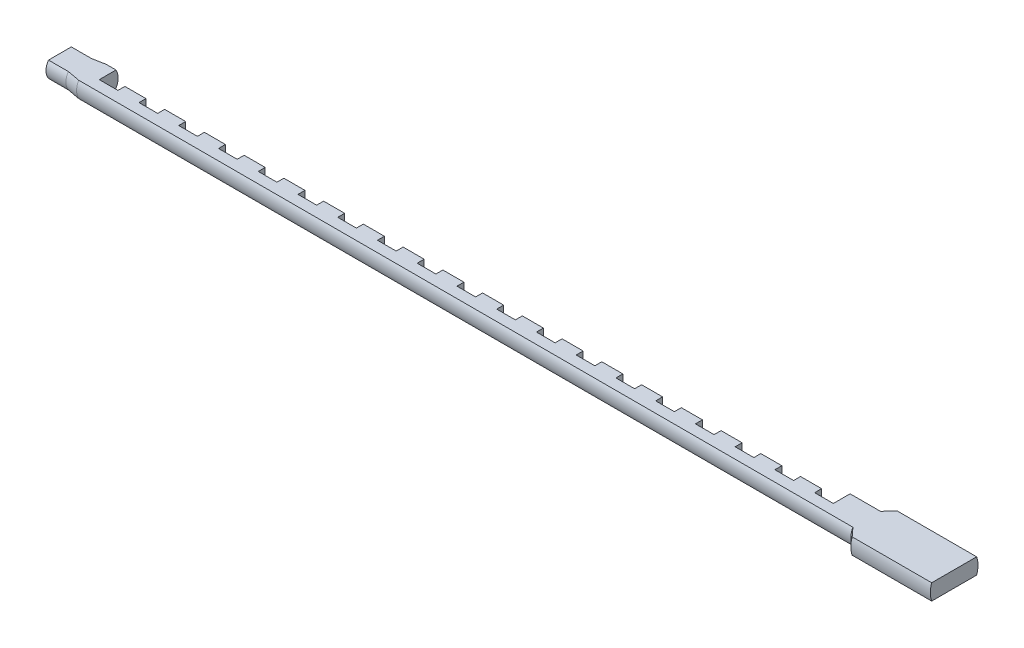
SolidWorks part; units mm, degrees
ref_plane "Front Plane" through (0, 0, 0) normal (0, 0, 1) x (1, 0, 0)
ref_plane "Top Plane" through (0, 0, 0) normal (0, 1, 0) x (1, 0, 0)
ref_plane "Right Plane" through (0, 0, 0) normal (1, 0, 0) x (0, 0, -1)
other "Configuration Table"
sketch "Sketch1" plane through (0, 0, 0) normal (0, 1, 0) x (1, 0, 0)
  line L0 (-125, 0) -> (100, 0) construction
  line L1 (-125, 0) -> (-125, 3.5)
  line L2 (-125, 3.5) -> (-120, 3.5)
  line L3 (-120, 3.5) -> (-116.8027, 4)
  line L4 (-116.8027, 4) -> (78, 4)
  line L6 (80, 6) -> (100, 6)
  line L7 (100, 6) -> (100, 0)
  line L8 (100, 0) -> (-125, 0)
  line L9 (78, 4) -> (80, 6)
  point P3 (90.4375, 2.5)
  point P10 (95.0649, 2.5)
  dimension "D1" = 125
  dimension "D2" = 100
  dimension "D3" = 3.5
  dimension "D4" = 5
  dimension "D5" = 4
  dimension "D6" = 20
  dimension "D7" = 6
  dimension "D8" = 45
revolve "Revolve1" add sketch "Sketch1" angle 360 about L0
sketch "Sketch3" plane through (0, 0, 0) normal (0, 1, 0) x (1, 0, 0)
  line L0 (-114.35, 4) -> (-114.35, -0.75)
  line L1 (78, 4) -> (-116.8027, 4) construction
  line L2 (-114.35, -0.75) -> (-109.65, -0.75)
  line L3 (-109.65, -0.75) -> (-109.65, 4)
  line L4 (-109.65, 4) -> (-114.35, 4)
  line L5 (-114.35, 4) -> (-109.65, -0.75) construction
  line L6 (-109.65, 4) -> (-114.35, -0.75) construction
  line L7 (-125, 3.5) -> (-125, -3.5) construction
  line L8 (-99.65, 4) -> (-104.35, 4)
  line L9 (-104.35, 4) -> (-104.35, -0.75)
  line L10 (-104.35, -0.75) -> (-99.65, -0.75)
  line L11 (-99.65, -0.75) -> (-99.65, 4)
  line L12 (-89.65, 4) -> (-94.35, 4)
  line L13 (-94.35, 4) -> (-94.35, -0.75)
  line L14 (-94.35, -0.75) -> (-89.65, -0.75)
  line L15 (-89.65, -0.75) -> (-89.65, 4)
  line L16 (-79.65, 4) -> (-84.35, 4)
  line L17 (-84.35, 4) -> (-84.35, -0.75)
  line L18 (-84.35, -0.75) -> (-79.65, -0.75)
  line L19 (-79.65, -0.75) -> (-79.65, 4)
  line L20 (-69.65, 4) -> (-74.35, 4)
  line L21 (-74.35, 4) -> (-74.35, -0.75)
  line L22 (-74.35, -0.75) -> (-69.65, -0.75)
  line L23 (-69.65, -0.75) -> (-69.65, 4)
  line L24 (-59.65, 4) -> (-64.35, 4)
  line L25 (-64.35, 4) -> (-64.35, -0.75)
  line L26 (-64.35, -0.75) -> (-59.65, -0.75)
  line L27 (-59.65, -0.75) -> (-59.65, 4)
  line L28 (-49.65, 4) -> (-54.35, 4)
  line L29 (-54.35, 4) -> (-54.35, -0.75)
  line L30 (-54.35, -0.75) -> (-49.65, -0.75)
  line L31 (-49.65, -0.75) -> (-49.65, 4)
  line L32 (-39.65, 4) -> (-44.35, 4)
  line L33 (-44.35, 4) -> (-44.35, -0.75)
  line L34 (-44.35, -0.75) -> (-39.65, -0.75)
  line L35 (-39.65, -0.75) -> (-39.65, 4)
  line L36 (-29.65, 4) -> (-34.35, 4)
  line L37 (-34.35, 4) -> (-34.35, -0.75)
  line L38 (-34.35, -0.75) -> (-29.65, -0.75)
  line L39 (-29.65, -0.75) -> (-29.65, 4)
  line L40 (-19.65, 4) -> (-24.35, 4)
  line L41 (-24.35, 4) -> (-24.35, -0.75)
  line L42 (-24.35, -0.75) -> (-19.65, -0.75)
  line L43 (-19.65, -0.75) -> (-19.65, 4)
  line L44 (-9.65, 4) -> (-14.35, 4)
  line L45 (-14.35, 4) -> (-14.35, -0.75)
  line L46 (-14.35, -0.75) -> (-9.65, -0.75)
  line L47 (-9.65, -0.75) -> (-9.65, 4)
  line L48 (0.35, 4) -> (-4.35, 4)
  line L49 (-4.35, 4) -> (-4.35, -0.75)
  line L50 (-4.35, -0.75) -> (0.35, -0.75)
  line L51 (0.35, -0.75) -> (0.35, 4)
  line L52 (10.35, 4) -> (5.65, 4)
  line L53 (5.65, 4) -> (5.65, -0.75)
  line L54 (5.65, -0.75) -> (10.35, -0.75)
  line L55 (10.35, -0.75) -> (10.35, 4)
  line L56 (20.35, 4) -> (15.65, 4)
  line L57 (15.65, 4) -> (15.65, -0.75)
  line L58 (15.65, -0.75) -> (20.35, -0.75)
  line L59 (20.35, -0.75) -> (20.35, 4)
  line L60 (30.35, 4) -> (25.65, 4)
  line L61 (25.65, 4) -> (25.65, -0.75)
  line L62 (25.65, -0.75) -> (30.35, -0.75)
  line L63 (30.35, -0.75) -> (30.35, 4)
  line L64 (40.35, 4) -> (35.65, 4)
  line L65 (35.65, 4) -> (35.65, -0.75)
  line L66 (35.65, -0.75) -> (40.35, -0.75)
  line L67 (40.35, -0.75) -> (40.35, 4)
  line L68 (50.35, 4) -> (45.65, 4)
  line L69 (45.65, 4) -> (45.65, -0.75)
  line L70 (45.65, -0.75) -> (50.35, -0.75)
  line L71 (50.35, -0.75) -> (50.35, 4)
  line L72 (60.35, 4) -> (55.65, 4)
  line L73 (55.65, 4) -> (55.65, -0.75)
  line L74 (55.65, -0.75) -> (60.35, -0.75)
  line L75 (60.35, -0.75) -> (60.35, 4)
  line L76 (70.35, 4) -> (65.65, 4)
  line L77 (65.65, 4) -> (65.65, -0.75)
  line L78 (65.65, -0.75) -> (70.35, -0.75)
  line L79 (70.35, -0.75) -> (70.35, 4)
  point P4 (-112, 1.625)
  dimension "D1" = 0.75
  dimension "D2" = 4.7
  dimension "D3" = 13
  dimension "D4" = 19
extrude "Cut-Extrude1" cut sketch "Sketch3" against normal through all both and the other way through all
sketch "Sketch4" plane through (0, 0, 0) normal (0, 1, 0) x (1, 0, 0)
  line L0 (70.35, 4) -> (70.35, -0.75) construction
  line L1 (-114.35, 4) -> (70.35, 4)
  line L2 (-114.35, 4) -> (-114.35, 1)
  line L3 (-114.35, 1) -> (70.35, 1)
  line L4 (70.35, 4) -> (70.35, 1)
  dimension "D1" = 3
extrude "Cut-Extrude2" cut sketch "Sketch4" against normal through all both and the other way through all
sketch "Sketch5" plane through (-125, 0, 0) normal (-1, 0, 0) x (0, 0, 1)
  line L9 (-7.674, -2) -> (7.7898, -2)
  line L10 (-7.674, -2) -> (-7.674, -7.0913)
  line L11 (-7.674, -7.0913) -> (7.7898, -7.0913)
  line L12 (7.7898, -2) -> (7.7898, -7.0913)
  line L13 (-7.674, 2) -> (7.7898, 2)
  line L14 (-7.674, 2) -> (-7.674, 7.3017)
  line L15 (-7.674, 7.3017) -> (7.7898, 7.3017)
  line L16 (7.7898, 2) -> (7.7898, 7.3017)
  dimension "D1" = 2
  dimension "D2" = 2
extrude "Cut-Extrude4" cut sketch "Sketch5" against normal through all both and the other way through all
